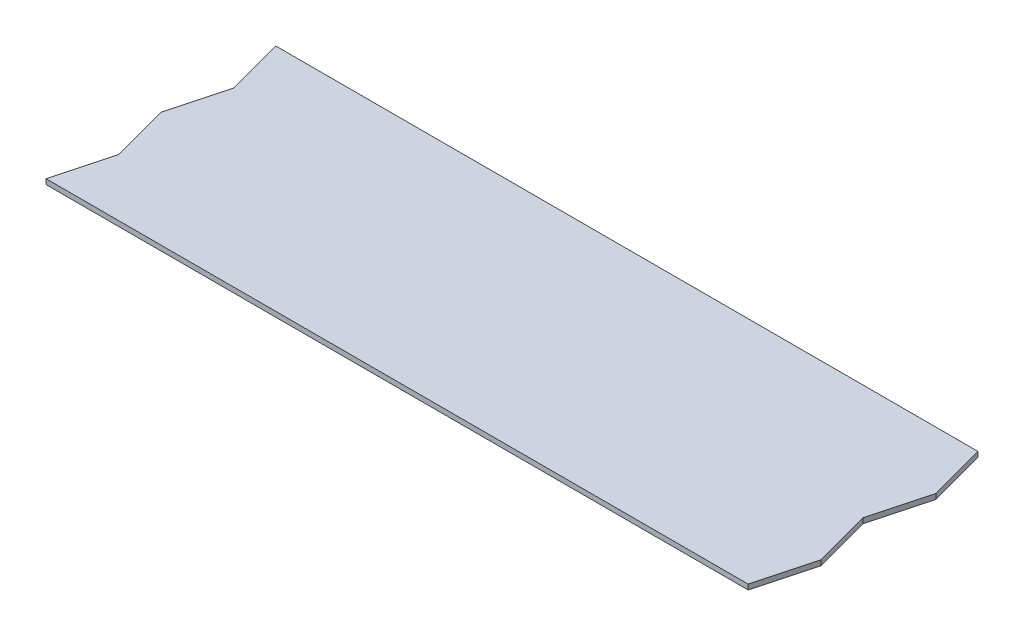
SolidWorks part; units mm, degrees
ref_plane "Front Plane" through (0, 0, 0) normal (0, 0, 1) x (1, 0, 0)
ref_plane "Top Plane" through (0, 0, 0) normal (0, 1, 0) x (1, 0, 0)
ref_plane "Right Plane" through (0, 0, 0) normal (1, 0, 0) x (0, 0, -1)
sketch "Sketch1" plane through (0, 0, 0) normal (0, 1, 0) x (1, 0, 0)
  line L0 (0, 0) -> (55, 0)
  line L1 (0, 0) -> (1.2058, -4.5)
  line L2 (55, -18) -> (0, -18)
  line L3 (1.2058, -4.5) -> (0, -9)
  line L4 (0, -9) -> (1.2058, -13.5)
  line L5 (1.2058, -13.5) -> (0, -18)
  line L6 (55, 0) -> (56.2058, -4.5)
  line L7 (56.2058, -4.5) -> (55, -9)
  line L8 (55, -9) -> (56.2058, -13.5)
  line L9 (56.2058, -13.5) -> (55, -18)
  point P3 (57.501, 0)
  point P7 (55.7067, -18)
  point P13 (55.5411, -18)
  point P15 (55.0468, -18)
  dimension "D1" = 75
  dimension "D2" = 75
  dimension "D4" = 18
  dimension "D5" = 55
  dimension "D3" = 2
  dimension "D6" = 2
extrude "Boss-Extrude1" add sketch "Sketch1" along normal blind 0.4
